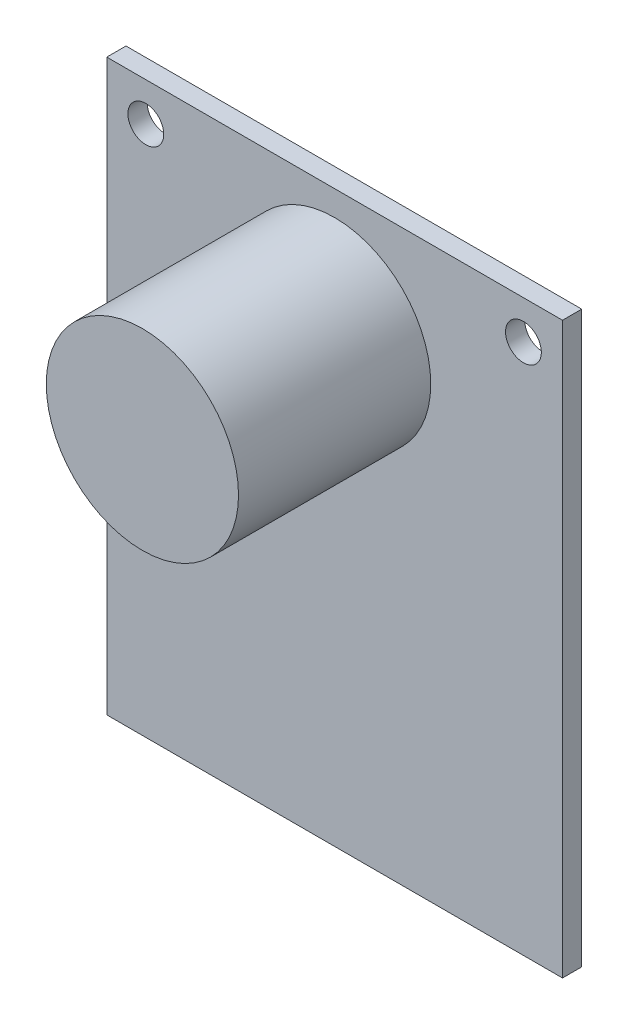
SolidWorks part; units mm, degrees
ref_plane "前视基准面" through (0, 0, 0) normal (0, 0, 1) x (1, 0, 0)
ref_plane "上视基准面" through (0, 0, 0) normal (0, 1, 0) x (1, 0, 0)
ref_plane "右视基准面" through (0, 0, 0) normal (1, 0, 0) x (0, 0, -1)
other "Configuration Table"
sketch "草图1" plane through (0, 0, 0) normal (0, 0, 1) x (1, 0, 0)
  line L0 (0, 0) -> (0, 48.8255) construction
  line L1 (-17.78, 44.45) -> (17.78, 44.45)
  line L2 (-17.78, 44.45) -> (-17.78, 0)
  line L3 (-17.78, 0) -> (17.78, 0)
  line L4 (17.78, 44.45) -> (17.78, 0)
  circle A0 centre (-14.732, 41.45) radius 1.397
  circle A1 centre (14.732, 41.45) radius 1.397
  point P4 (0, 0)
  dimension "D4" = 2.794
  dimension "D1" = 35.56
  dimension "D2" = 44.45
  dimension "D3" = 29.464
  dimension "D5" = 3
extrude "凸台-拉伸1" add sketch "草图1" along normal blind 1.5
sketch "草图2" plane through (0, 0, 1.5) normal (0, 0, 1) x (1, 0, 0)
  circle A0 centre (0, 35) radius 7.5
  point P2 (0, 0)
  point P4 (0, 30)
  dimension "D1" = 15
  dimension "D2" = 35
extrude "凸台-拉伸2" add sketch "草图2" along normal blind 15
